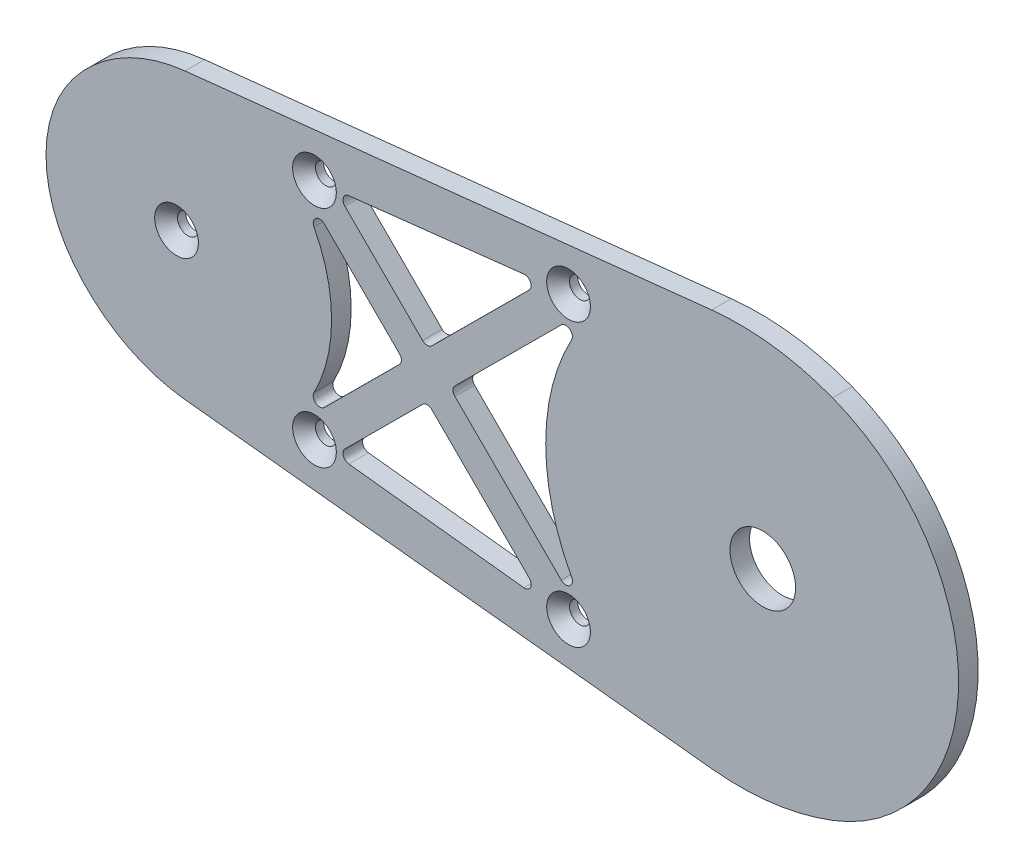
SolidWorks part; units mm, degrees
material "5052-O"
ref_plane "正面" through (0, 0, 0) normal (0, 0, 1) x (1, 0, 0)
ref_plane "平面" through (0, 0, 0) normal (0, 1, 0) x (1, 0, 0)
ref_plane "右側面" through (0, 0, 0) normal (1, 0, 0) x (0, 0, -1)
sketch "ｽｹｯﾁ1" plane through (0, 0, 0) normal (0, 0, 1) x (1, 0, 0)
  line L0 (-2.2272, 19.8756) -> (86.4592, 29.8134)
  line L2 (86.4592, -29.8134) -> (-2.2272, -19.8756)
  line L3 (0, 0) -> (89.8, 0) construction
  arc A0 (-2.2272, 19.8756) -> (-2.2272, -19.8756) centre (0, 0) ccw
  arc A1 (86.4592, -29.8134) -> (86.4592, 29.8134) centre (89.8, 0) ccw
  circle A2 centre (0, 0) radius 1.6
  circle A3 centre (89.8, 0) radius 5.025
  dimension "D1" = 20
  dimension "D2" = 30
  dimension "D4" = 3.2
  dimension "D5" = 10.05
  dimension "D3" = 89.8
extrude "ﾎﾞｽ - 押し出し1" add sketch "ｽｹｯﾁ1" along normal blind 3
sketch "ｽｹｯﾁ2" plane through (0, 0, 3) normal (0, 0, 1) x (1, 0, 0)
  line L0 (86.4592, 29.8134) -> (-2.2272, 19.8756) construction
  line L1 (-2.2272, -19.8756) -> (86.4592, -29.8134) construction
  line L2 (21.1278, -17.2098) -> (60.0467, -21.5709) construction
  line L3 (21.1278, 17.2098) -> (60.0467, 21.5709) construction
  line L4 (21.1278, 17.2098) -> (21.1278, -17.2098) construction
  line L5 (60.0467, 21.5709) -> (60.0467, -21.5709) construction
  line L6 (24.3116, -17.5666) -> (56.0561, -21.1237)
  line L7 (24.3116, 17.5666) -> (56.0561, 21.1237)
  line L8 (21.1278, 17.2098) -> (60.0467, -21.5709) construction
  line L9 (60.0467, 21.5709) -> (21.1278, -17.2098) construction
  line L10 (34.8571, 0) -> (22.64, -12.1737)
  line L11 (34.8571, 0) -> (22.64, 12.1737)
  line L12 (56.0561, 21.1237) -> (38.399, 3.5293)
  line L13 (38.399, 3.5293) -> (24.3116, 17.5666)
  line L14 (24.3116, -17.5666) -> (38.399, -3.5293)
  line L15 (38.399, -3.5293) -> (56.0561, -21.1237)
  line L16 (58.9271, 16.926) -> (41.9408, 0)
  line L17 (41.9408, 0) -> (58.9271, -16.926)
  arc A0 (10.5019, 21.302) -> (10.5019, -21.302) centre (0, 0) cw construction
  arc A1 (100.7075, 31.41) -> (100.7075, -31.41) centre (89.8, 0) ccw construction
  arc A2 (16.1662, 21.9367) -> (16.1662, -21.9367) centre (0, 0) cw construction
  arc A3 (65.3648, 27.4497) -> (65.3648, -27.4497) centre (89.8, 0) ccw construction
  circle A4 centre (21.1278, 17.2098) radius 1.6
  circle A5 centre (21.1278, -17.2098) radius 1.6
  circle A6 centre (60.0467, -21.5709) radius 1.6
  circle A7 centre (60.0467, 21.5709) radius 1.6
  arc A8 (21.048, 11.0021) -> (21.048, -11.0021) centre (0, 0) cw
  arc A9 (60.5138, 15.7441) -> (60.5138, -15.7441) centre (89.8, 0) ccw
  arc A16 (22.64, 12.1737) -> (21.048, 11.0021) centre (21.9342, 11.4653) ccw
  arc A19 (21.048, -11.0021) -> (22.64, -12.1737) centre (21.9342, -11.4653) ccw
  arc A20 (58.9271, -16.926) -> (60.5138, -15.7441) centre (59.633, -16.2177) ccw
  arc A21 (60.5138, 15.7441) -> (58.9271, 16.926) centre (59.633, 16.2177) ccw
  dimension "D1" = 33.25
  dimension "D2" = 23.75
  dimension "D3" = 3.5
  dimension "D4" = 3.5
  dimension "D7" = 3.2
  dimension "D8" = 5
  dimension "D14" = 1
  dimension "D5" = 5.25
  dimension "D6" = 5.25
  dimension "D10" = 5
  dimension "D11" = 5
  dimension "D12" = 5
  dimension "D13" = 5
extrude "ｶｯﾄ - 押し出し1" cut sketch "ｽｹｯﾁ2" against normal through all
fillet "ﾌｨﾚｯﾄ1" radius 1 8 edges at (24.3116, -17.5666, 1.5) (38.399, -3.5293, 1.5) (56.0561, -21.1237, 1.5) (34.8571, 0, 1.5) (24.3116, 17.5666, 1.5) (56.0561, 21.1237, 1.5) (41.9408, 0, 1.5) (38.399, 3.5293, 1.5)
sketch "ｽｹｯﾁ3" plane through (0, 0, 3) normal (0, 0, 1) x (1, 0, 0)
  line L0 (-2.3694, 22.1537) -> (86.415, 31.6495) construction
  line L1 (0, 0) -> (89.8, 0) construction
  line L2 (86.415, -31.6495) -> (-2.3694, -22.1537) construction
  line L3 (-2.6098, 24.4008) -> (86.1746, 33.8967) construction
  line L4 (86.1746, -33.8967) -> (-2.6098, -24.4008) construction
  line L5 (1.2983, 21.8017) -> (81.9794, 30.4309)
  line L6 (86.4592, 29.8134) -> (-2.2272, 19.8756)
  line L7 (1.2983, -21.8017) -> (81.9794, -30.4309)
  line L8 (86.4592, -29.8134) -> (-2.2272, -19.8756)
  arc A0 (86.415, 31.6495) -> (86.415, -31.6495) centre (89.8, 0) cw construction
  arc A1 (-2.3694, 22.1537) -> (-2.3694, -22.1537) centre (0, 0) ccw construction
  arc A2 (81.9794, 30.4309) -> (100.5002, 28.0269) centre (86.2333, -9.3423) cw
  arc A3 (86.1746, 33.8967) -> (86.1746, -33.8967) centre (89.8, 0) cw construction
  arc A4 (-2.6098, 24.4008) -> (-2.6098, -24.4008) centre (0, 0) ccw construction
  arc A5 (1.2983, 21.8017) -> (-15.8279, 12.2261) centre (3.957, -3.0565) ccw
  arc A6 (-15.8279, 12.2261) -> (-2.2272, 19.8756) centre (0, 0) cw
  arc A7 (86.4592, 29.8134) -> (100.5002, 28.0269) centre (89.8, 0) cw
  arc A8 (81.9794, -30.4309) -> (100.5002, -28.0269) centre (86.2333, 9.3423) ccw
  arc A9 (86.4592, -29.8134) -> (100.5002, -28.0269) centre (89.8, 0) ccw
  arc A10 (1.2983, -21.8017) -> (-15.8279, -12.2261) centre (3.957, 3.0565) cw
  arc A11 (-15.8279, -12.2261) -> (-2.2272, -19.8756) centre (0, 0) ccw
  circle A12 centre (89.8, 0) radius 5.025 construction
  arc A13 (-2.2272, 19.8756) -> (-2.2272, -19.8756) centre (0, 0) ccw construction
  arc A14 (86.4592, -29.8134) -> (86.4592, 29.8134) centre (89.8, 0) ccw construction
  dimension "D1" = 22.28
  dimension "D2" = 31.83
  dimension "D4" = 25
  dimension "D5" = 40
  dimension "D6" = 2.26
  dimension "D7" = 2.26
  dimension "D3" = 6
extrude "ﾎﾞｽ - 押し出し2" add sketch "ｽｹｯﾁ3" against normal up to surface (3 mm away) up to face at (22.7278, 17.2098, 0)
chamfer "面取り1" distance 1.75 angle 45 5 edges at (61.6467, 21.5709, 3) (22.7278, 17.2098, 3) (22.7278, -17.2098, 3) (1.6, 0, 3) (61.6467, -21.5709, 3)
